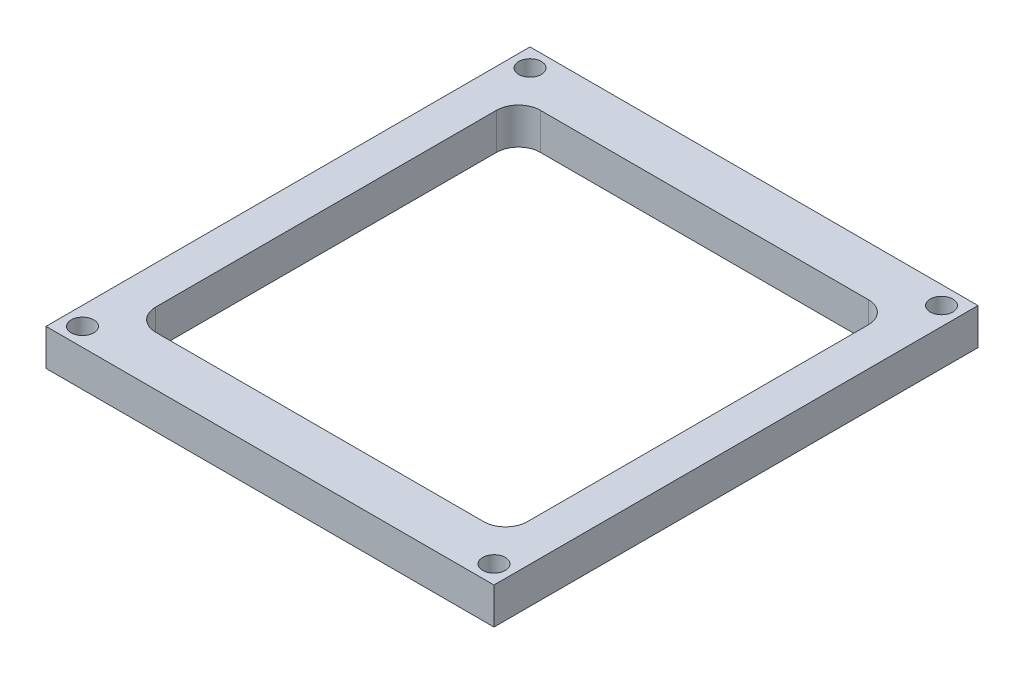
SolidWorks part; units mm, degrees
ref_plane "Front Plane" through (0, 0, 0) normal (0, 0, 1) x (1, 0, 0)
ref_plane "Top Plane" through (0, 0, 0) normal (0, 1, 0) x (1, 0, 0)
ref_plane "Right Plane" through (0, 0, 0) normal (1, 0, 0) x (0, 0, -1)
sketch "Sketch1" plane through (0, 0, 0) normal (0, 1, 0) x (1, 0, 0)
  line L0 (-20.9808, 29.1861) -> (40.4192, 29.1861)
  line L1 (-20.9808, 29.1861) -> (-20.9808, -37.1539)
  line L2 (-20.9808, -37.1539) -> (40.4192, -37.1539)
  line L3 (40.4192, 29.1861) -> (40.4192, -37.1539)
  line L4 (-20.9808, -3.9839) -> (40.4192, -3.9839) construction
  line L5 (9.7192, 29.1861) -> (9.7192, -37.1539) construction
  line L7 (-12.7558, -30.3389) -> (32.1942, -30.3389)
  line L8 (-15.7558, -27.3389) -> (-15.7558, 19.3711)
  line L9 (-12.7558, 22.3711) -> (32.1942, 22.3711)
  line L10 (35.1942, -27.3389) -> (35.1942, 19.3711)
  line L11 (-15.7558, -30.3389) -> (35.1942, 22.3711) construction
  line L12 (-15.7558, 22.3711) -> (35.1942, -30.3389) construction
  circle A0 centre (-18.4808, 26.6861) radius 1.55
  circle A1 centre (37.9192, 26.6861) radius 1.55
  circle A2 centre (37.9192, -34.6539) radius 1.55
  circle A3 centre (-18.4808, -34.6539) radius 1.55
  arc A4 (32.1942, -30.3389) -> (35.1942, -27.3389) centre (32.1942, -27.3389) ccw
  arc A5 (-12.7558, -30.3389) -> (-15.7558, -27.3389) centre (-12.7558, -27.3389) cw
  arc A6 (-15.7558, 19.3711) -> (-12.7558, 22.3711) centre (-12.7558, 19.3711) cw
  arc A7 (32.1942, 22.3711) -> (35.1942, 19.3711) centre (32.1942, 19.3711) cw
  point P16 (9.7192, -3.9839)
  dimension "D3" = 2.5
  dimension "D5" = 3.1
  dimension "D12" = 3
  dimension "D1" = 61.4
  dimension "D2" = 66.34
  dimension "D4" = 2.5
  dimension "D6" = 5.225
  dimension "D7" = 52.71
  dimension "D13" = 5.225
extrude "Boss-Extrude1" add sketch "Sketch1" along normal blind 5
